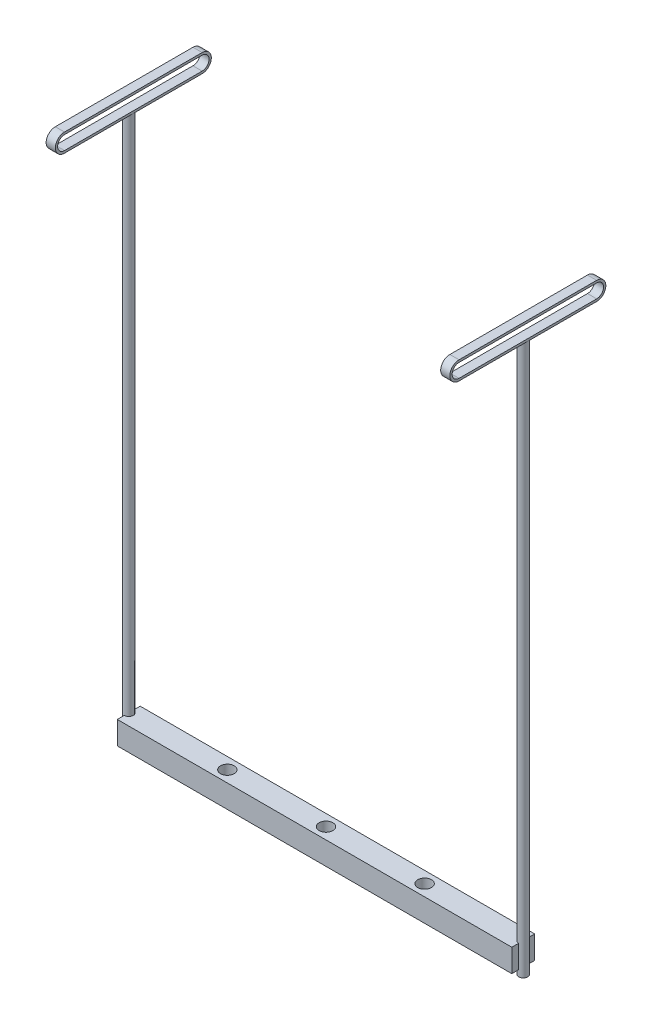
SolidWorks part; units mm, degrees
ref_plane "Front Plane" through (0, 0, 0) normal (0, 0, 1) x (1, 0, 0)
ref_plane "Top Plane" through (0, 0, 0) normal (0, 1, 0) x (1, 0, 0)
ref_plane "Right Plane" through (0, 0, 0) normal (1, 0, 0) x (0, 0, -1)
sketch "Sketch1" plane through (0, 0, 0) normal (1, 0, 0) x (0, 0, -1)
  line L0 (0, 0) -> (0, 15) construction
  line L1 (-150, 15) -> (150, 15)
  line L2 (150, -15) -> (-150, -15)
  line L3 (150, -20) -> (-150, -20)
  line L4 (-150, 20) -> (150, 20)
  arc A0 (150, 15) -> (150, -15) centre (150, 0) cw
  arc A1 (-150, 15) -> (-150, -15) centre (-150, 0) ccw
  arc A2 (-150, 20) -> (-150, -20) centre (-150, 0) ccw
  arc A3 (150, 20) -> (150, -20) centre (150, 0) cw
  point P10 (0, -15)
  dimension "D2" = 15
  dimension "D1" = 15
  dimension "D3" = 150
  dimension "D4" = 150
  dimension "D5" = 5
extrude "Boss-Extrude1" add sketch "Sketch1" along normal mid plane 20
sketch "Sketch2" plane through (0, -20, 0) normal (0, -1, 0) x (1, 0, 0)
  circle A0 centre (0, 0) radius 10
  dimension "D1" = 20
extrude "Boss-Extrude2" add sketch "Sketch2" along normal blind 1200
sketch "Sketch4" plane through (0, 0, 0) normal (1, 0, 0) x (0, 0, -1)
  line L0 (0, 0) -> (0, -1278.9451) construction
  line L2 (-25, -1156.4138) -> (25, -1156.4138)
  line L3 (-25, -1156.4138) -> (-25, -1206.4138)
  line L4 (-25, -1206.4138) -> (25, -1206.4138)
  line L5 (25, -1156.4138) -> (25, -1206.4138)
  line L6 (-25, -1156.4138) -> (25, -1206.4138) construction
  line L7 (-25, -1206.4138) -> (25, -1156.4138) construction
  point P3 (0, -1181.4138)
  dimension "D1" = 50
  dimension "D2" = 50
extrude "Boss-Extrude3" add sketch "Sketch4" against normal blind 860
sketch "Sketch6" plane through (0, -1156.4138, 0) normal (0, 1, 0) x (1, 0, 0)
  line L0 (-860, 0) -> (-645, 0) construction
  line L1 (-860, 25) -> (-860, -25) construction
  circle A0 centre (-645, 0) radius 15
  circle A1 centre (-430, 0) radius 15
  circle A2 centre (-215, 0) radius 15
  dimension "D2" = 30
  dimension "D1" = 215
  dimension "D3" = 3
extrude "Cut-Extrude2" cut sketch "Sketch6" against normal through all both and the other way through all
ref_plane "Plane1" through (-430, 0, 0) normal (1, 0, 0) x (0, 0, -1)
mirror "Mirror1" about plane through (-430, 0, 0) normal (1, 0, 0) of "Boss-Extrude1", "Boss-Extrude2"
mirror "Mirror2" about plane through (-430, 0, 0) normal (1, 0, 0) of "Boss-Extrude1"
